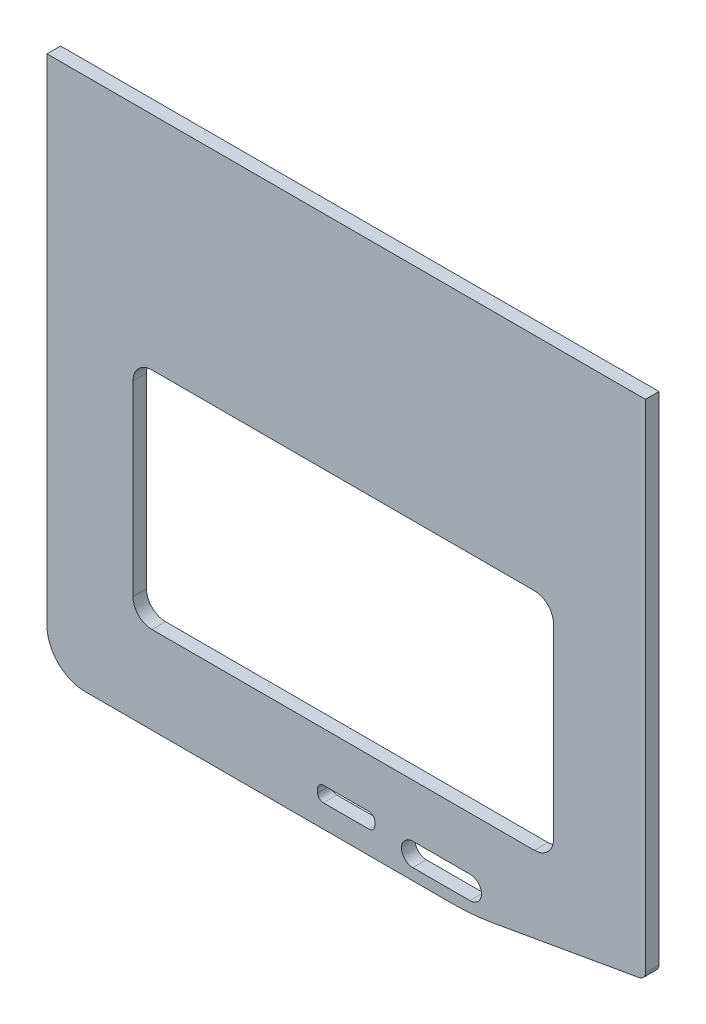
SolidWorks part; units mm, degrees
material "E-Glass Fiber"
ref_plane "Front Plane" through (0, 0, 0) normal (0, 0, 1) x (1, 0, 0)
ref_plane "Top Plane" through (0, 0, 0) normal (0, 1, 0) x (1, 0, 0)
ref_plane "Right Plane" through (0, 0, 0) normal (1, 0, 0) x (0, 0, -1)
sketch "Sketch1" plane through (0, 0, 0) normal (0, 0, -1) x (1, 0, 0)
  line L0 (0, -4.2398) -> (0, 81.0142) construction
  line L2 (0, -55) -> (0, 55) construction
  line L4 (-3381.666, 0) -> (-1328.9091, 0) construction
  line L5 (-157.112, -260) -> (-157.112, 20)
  line L6 (157.112, -260) -> (-157.112, -260)
  line L7 (157.112, -260) -> (157.112, 20)
  line L8 (157.112, 20) -> (-157.112, 20)
  line L10 (-55, 0) -> (55, 0) construction
  point P13 (0, -260)
  dimension "D1" = 314.224
  dimension "D2" = 280
  dimension "D3" = 20
extrude "Boss-Extrude1" add sketch "Sketch1" along normal blind 7.112
sketch "Sketch2" plane through (0, 0, 0) normal (0, 0, 1) x (1, 0, 0)
  line L1 (-101.9855, 143.8175) -> (98.8039, 143.8175)
  line L2 (-111.9855, 133.8175) -> (-111.9855, 35.798)
  line L3 (-101.9855, 25.798) -> (98.8039, 25.798)
  line L4 (108.8039, 133.8175) -> (108.8039, 35.798)
  arc A0 (-111.9855, 35.798) -> (-101.9855, 25.798) centre (-101.9855, 35.798) ccw
  arc A1 (98.8039, 25.798) -> (108.8039, 35.798) centre (98.8039, 35.798) ccw
  arc A2 (98.8039, 143.8175) -> (108.8039, 133.8175) centre (98.8039, 133.8175) cw
  arc A3 (-101.9855, 143.8175) -> (-111.9855, 133.8175) centre (-101.9855, 133.8175) ccw
  dimension "D1" = 10
extrude "Cut-Extrude1" cut sketch "Sketch2" against normal through all and the other way through all
sketch "Sketch3" plane through (0, 0, 0) normal (0, 0, 1) x (1, 0, 0)
  line L0 (0, -55) -> (0, 55) construction
  line L1 (-12, -8) -> (12, -8)
  line L2 (-15, -5) -> (-15, -3)
  line L3 (-12, 0) -> (12, 0)
  line L4 (0, -6.5559) -> (0, 7.9335) construction
  line L6 (55, 0) -> (-55, 0) construction
  line L7 (15, -5) -> (15, -3)
  arc A0 (-12, -8) -> (-15, -5) centre (-12, -5) cw
  arc A1 (-15, -3) -> (-12, 0) centre (-12, -3) cw
  arc A2 (15, -3) -> (12, 0) centre (12, -3) ccw
  arc A3 (12, -8) -> (15, -5) centre (12, -5) ccw
  point P1 (0, -8)
  point P20 (0, 0)
  dimension "D1" = 3
  dimension "D2" = 8
  dimension "D3" = 30
extrude "Cut-Extrude2" cut sketch "Sketch3" against normal through all
sketch "Sketch4" plane through (0, 0, 0) normal (0, 0, 1) x (1, 0, 0)
  line L0 (66.3715, -20) -> (157.112, -4)
  line L1 (157.112, -20) -> (-157.112, -20) construction
  line L2 (157.112, 260) -> (157.112, -20) construction
  line L3 (157.112, -4) -> (157.112, -20)
  line L4 (157.112, -20) -> (66.3715, -20)
  dimension "D1" = 10
  dimension "D2" = 16
extrude "Cut-Extrude3" cut sketch "Sketch4" against normal through all
fillet "Fillet1" radius 120 1 edges at (66.3715, -20, -3.556)
fillet "Fillet2" radius 20 1 edges at (-157.112, -20, -3.556)
fillet "Fillet3" radius 4 1 edges at (157.112, -4, -3.556)
sketch "Sketch5" plane through (0, 0, 0) normal (0, 0, 1) x (1, 0, 0)
  line L0 (3.9116, 0) -> (-3.9116, 0) construction
  line L1 (35, -8) -> (65, -8) construction
  line L2 (35, -2) -> (65, -2)
  line L3 (35, -14) -> (65, -14)
  line L5 (0, -3.9116) -> (0, 3.9116) construction
  arc A0 (35, -2) -> (35, -14) centre (35, -8) ccw
  arc A1 (65, -14) -> (65, -2) centre (65, -8) ccw
  point P0 (50, -8)
  dimension "D2" = 6
  dimension "D1" = 2
  dimension "D3" = 30
  dimension "D4" = 50
extrude "Cut-Extrude4" cut sketch "Sketch5" against normal through all
